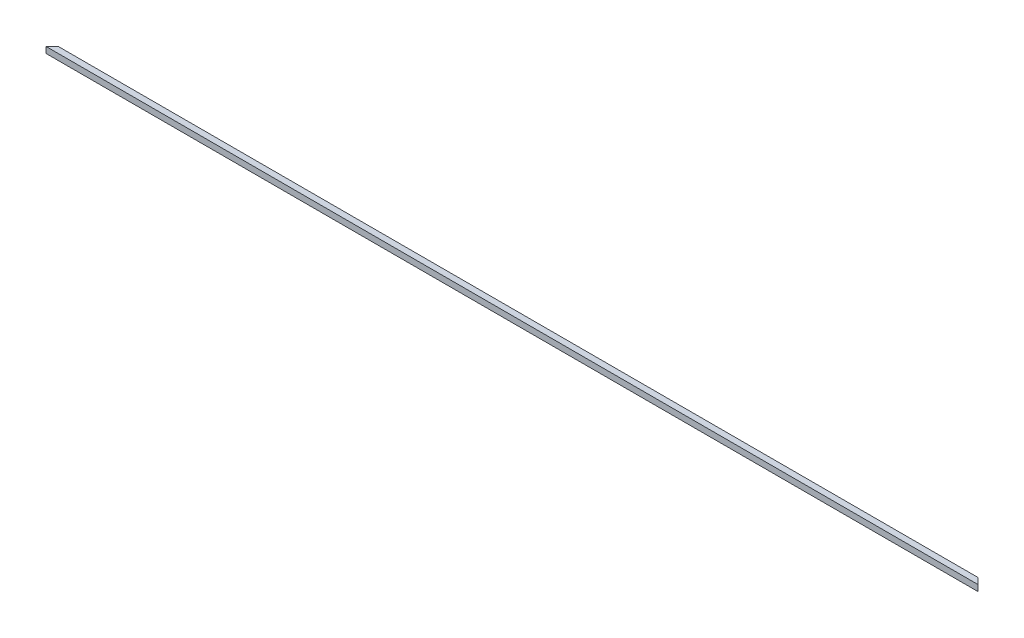
SolidWorks part; units mm, degrees
ref_plane "Front Plane" through (0, 0, 0) normal (0, 0, 1) x (1, 0, 0)
ref_plane "Top Plane" through (0, 0, 0) normal (0, 1, 0) x (1, 0, 0)
ref_plane "Right Plane" through (0, 0, 0) normal (1, 0, 0) x (0, 0, -1)
sketch "Sketch1" plane through (0, 0, 0) normal (0, 1, 0) x (1, 0, 0)
  line L0 (0, 0) -> (3048, 0)
  line L1 (3048, 0) -> (3028, 20)
  line L2 (3028, 20) -> (20, 20)
  line L3 (20, 20) -> (0, 0)
  dimension "D1" = 3048
  dimension "D2" = 45
  dimension "D3" = 45
  dimension "D4" = 20
extrude "Boss-Extrude1" add sketch "Sketch1" along normal blind 20
